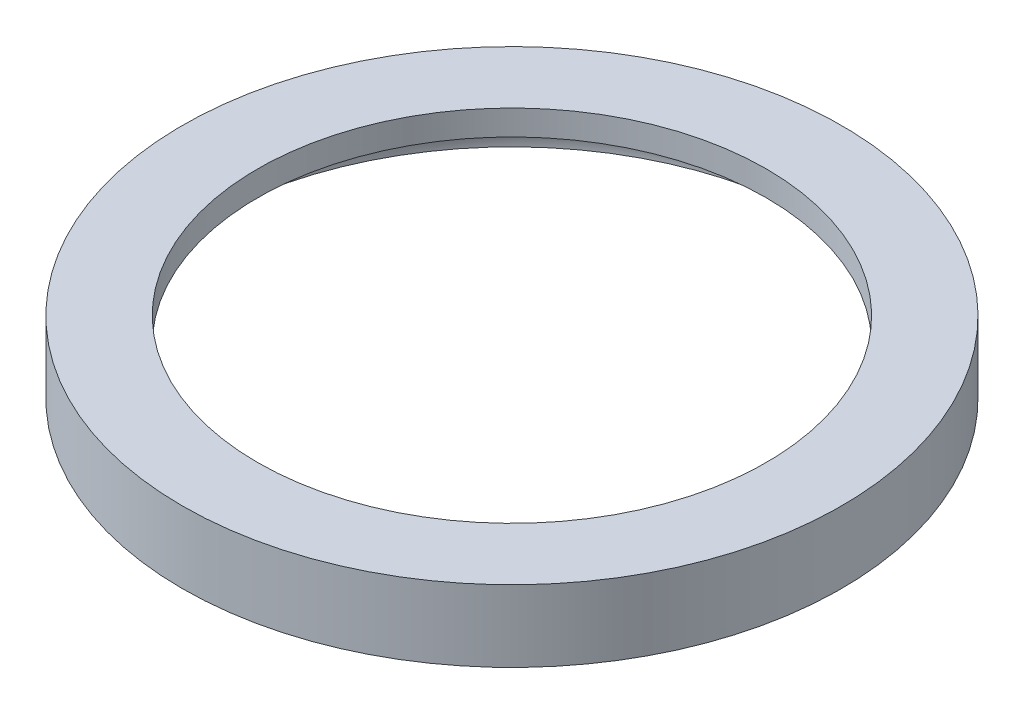
SolidWorks part; units mm, degrees
material "AISI 316 Stainless Steel Sheet (SS)"
ref_plane "Front Plane" through (0, 0, 0) normal (0, 0, 1) x (1, 0, 0)
ref_plane "Top Plane" through (0, 0, 0) normal (0, 1, 0) x (1, 0, 0)
ref_plane "Right Plane" through (0, 0, 0) normal (1, 0, 0) x (0, 0, -1)
sketch "Sketch1" plane through (0, 0, 0) normal (1, 0, 0) x (0, 0, -1)
  line L0 (-35.5, 4.5067) -> (-46, 4.5067)
  line L1 (-46, 4.5067) -> (-46, -5.4933)
  line L2 (-46, -5.4933) -> (-43, -5.4933)
  line L3 (-36.5, 1.0067) -> (-35.5, 1.0067)
  line L4 (-35.5, 1.0067) -> (-35.5, 4.5067)
  line L5 (0, 9.3262) -> (0, -8.5006) construction
  arc A0 (-43, -5.4933) -> (-36.5, 1.0067) centre (-36.5, -5.4933) cw
  dimension "D1" = 6.5
  dimension "D2" = 1
  dimension "D3" = 10
  dimension "D4" = 46
  dimension "D5" = 10
  dimension "D6" = 92
  dimension "D7" = 71
revolve "Revolve1" add sketch "Sketch1" angle 360 about L5
